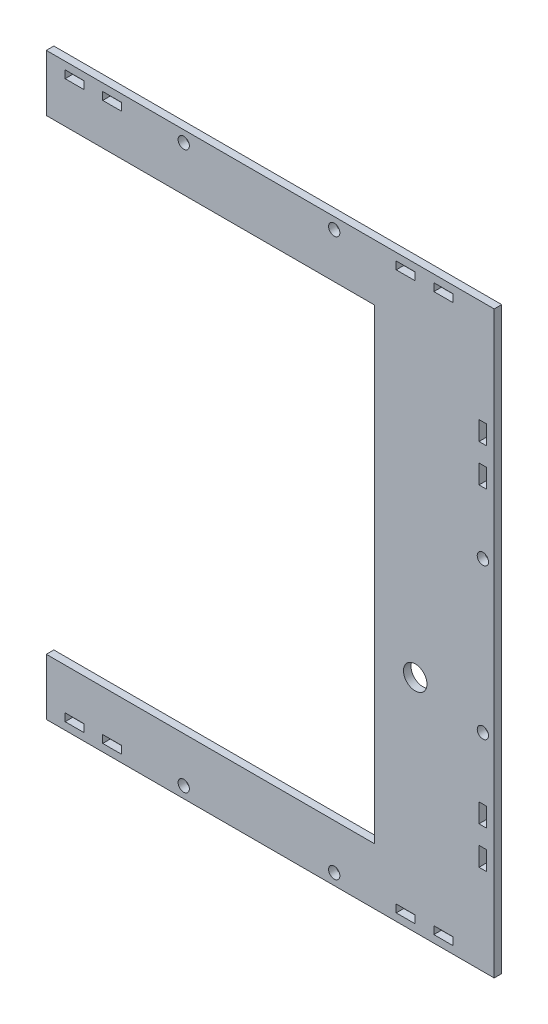
SolidWorks part; units mm, degrees
ref_plane "前视基准面" through (0, 0, 0) normal (0, 0, 1) x (1, 0, 0)
ref_plane "上视基准面" through (0, 0, 0) normal (0, 1, 0) x (1, 0, 0)
ref_plane "右视基准面" through (0, 0, 0) normal (1, 0, 0) x (0, 0, -1)
sketch "草图1" plane through (0, 0, 0) normal (0, 0, 1) x (1, 0, 0)
  line L0 (-46.0613, -2.3972) -> (-51.1113, -0.3472) construction
  line L5 (36.8887, -0.3472) -> (41.9387, -0.3472)
  line L6 (36.8887, -0.3472) -> (36.8887, -2.3972)
  line L11 (36.8887, -2.3972) -> (41.9387, -2.3972)
  line L12 (41.9387, -0.3472) -> (41.9387, -2.3972)
  line L13 (36.8887, -0.3472) -> (41.9387, -2.3972) construction
  line L14 (36.8887, -2.3972) -> (41.9387, -0.3472) construction
  line L15 (46.8887, -0.3472) -> (51.9387, -0.3472)
  line L25 (46.8887, -0.3472) -> (46.8887, -2.3972)
  line L30 (46.8887, -2.3972) -> (51.9387, -2.3972)
  line L31 (51.9387, -0.3472) -> (51.9387, -2.3972)
  line L36 (46.8887, -0.3472) -> (51.9387, -2.3972) construction
  line L37 (46.8887, -2.3972) -> (51.9387, -0.3472) construction
  line L38 (-46.0613, -0.3472) -> (-51.1113, -2.3972) construction
  line L39 (-36.0613, -2.3972) -> (-41.1113, -0.3472) construction
  line L40 (-36.0613, -0.3472) -> (-41.1113, -2.3972) construction
  line L55 (-51.1113, -0.3472) -> (-51.1113, -2.3972)
  line L60 (-46.0613, -2.3972) -> (-51.1113, -2.3972)
  line L61 (-46.0613, -0.3472) -> (-46.0613, -2.3972)
  line L66 (-46.0613, -0.3472) -> (-51.1113, -0.3472)
  line L67 (-41.1113, -0.3472) -> (-41.1113, -2.3972)
  line L68 (-36.0613, -2.3972) -> (-41.1113, -2.3972)
  line L69 (-36.0613, -0.3472) -> (-36.0613, -2.3972)
  line L70 (-36.0613, -0.3472) -> (-41.1113, -0.3472)
  line L81 (-48.5863, -1.3722) -> (49.4137, -1.3722) construction
  line L82 (-19.5863, -149.3722) -> (-8.6103, -149.3722) construction
  line L83 (-46.0613, -150.3972) -> (-51.1113, -148.3472) construction
  line L84 (36.8887, -148.3472) -> (41.9387, -148.3472)
  line L85 (36.8887, -148.3472) -> (36.8887, -150.3972)
  line L86 (36.8887, -150.3972) -> (41.9387, -150.3972)
  line L87 (41.9387, -148.3472) -> (41.9387, -150.3972)
  line L88 (36.8887, -148.3472) -> (41.9387, -150.3972) construction
  line L89 (36.8887, -150.3972) -> (41.9387, -148.3472) construction
  line L90 (46.8887, -148.3472) -> (51.9387, -148.3472)
  line L91 (46.8887, -148.3472) -> (46.8887, -150.3972)
  line L92 (46.8887, -150.3972) -> (51.9387, -150.3972)
  line L93 (51.9387, -148.3472) -> (51.9387, -150.3972)
  line L94 (46.8887, -148.3472) -> (51.9387, -150.3972) construction
  line L95 (46.8887, -150.3972) -> (51.9387, -148.3472) construction
  line L96 (-46.0613, -148.3472) -> (-51.1113, -150.3972) construction
  line L97 (-36.0613, -150.3972) -> (-41.1113, -148.3472) construction
  line L98 (-36.0613, -148.3472) -> (-41.1113, -150.3972) construction
  line L99 (-51.1113, -148.3472) -> (-51.1113, -150.3972)
  line L100 (-46.0613, -150.3972) -> (-51.1113, -150.3972)
  line L101 (-46.0613, -148.3472) -> (-46.0613, -150.3972)
  line L102 (-46.0613, -148.3472) -> (-51.1113, -148.3472)
  line L103 (-41.1113, -148.3472) -> (-41.1113, -150.3972)
  line L104 (-36.0613, -150.3972) -> (-41.1113, -150.3972)
  line L105 (-36.0613, -148.3472) -> (-36.0613, -150.3972)
  line L106 (-36.0613, -148.3472) -> (-41.1113, -148.3472)
  line L107 (59.9198, -57.3722) -> (59.9198, -97.3722) construction
  line L108 (-56.1113, -13.3722) -> (31.071, -13.3722)
  line L109 (-56.1113, 1.6278) -> (62.9198, 1.6278)
  line L110 (-56.1113, 1.6278) -> (-56.1113, -152.3722) construction
  line L111 (-56.1113, -152.3722) -> (62.9198, -152.3722) construction
  line L112 (62.9198, 1.6278) -> (62.9198, -152.3722)
  line L113 (60.9448, -123.8472) -> (58.8948, -128.8972) construction
  line L114 (58.8948, -40.8972) -> (58.8948, -35.8472)
  line L115 (58.8948, -40.8972) -> (60.9448, -40.8972)
  line L116 (60.9448, -40.8972) -> (60.9448, -35.8472)
  line L117 (58.8948, -35.8472) -> (60.9448, -35.8472)
  line L118 (58.8948, -40.8972) -> (60.9448, -35.8472) construction
  line L119 (60.9448, -40.8972) -> (58.8948, -35.8472) construction
  line L120 (58.8948, -30.8972) -> (58.8948, -25.8472)
  line L121 (58.8948, -30.8972) -> (60.9448, -30.8972)
  line L122 (60.9448, -30.8972) -> (60.9448, -25.8472)
  line L123 (58.8948, -25.8472) -> (60.9448, -25.8472)
  line L124 (58.8948, -30.8972) -> (60.9448, -25.8472) construction
  line L125 (60.9448, -30.8972) -> (58.8948, -25.8472) construction
  line L126 (58.8948, -123.8472) -> (60.9448, -128.8972) construction
  line L127 (60.9448, -113.8472) -> (58.8948, -118.8972) construction
  line L128 (58.8948, -113.8472) -> (60.9448, -118.8972) construction
  line L129 (58.8948, -128.8972) -> (60.9448, -128.8972)
  line L130 (60.9448, -123.8472) -> (60.9448, -128.8972)
  line L131 (58.8948, -123.8472) -> (60.9448, -123.8472)
  line L132 (58.8948, -123.8472) -> (58.8948, -128.8972)
  line L133 (58.8948, -118.8972) -> (60.9448, -118.8972)
  line L134 (60.9448, -113.8472) -> (60.9448, -118.8972)
  line L135 (58.8948, -113.8472) -> (60.9448, -113.8472)
  line L136 (58.8948, -113.8472) -> (58.8948, -118.8972)
  line L137 (31.071, -13.3722) -> (31.071, -137.3722)
  line L138 (31.071, -137.3722) -> (-56.1113, -137.3722)
  line L139 (-56.1113, -137.3722) -> (-56.1113, -152.3722)
  line L140 (-56.1113, -13.3722) -> (-56.1113, 1.6278)
  line L141 (62.9198, -152.3722) -> (-56.1113, -152.3722)
  circle A6 centre (-19.5863, -1.3722) radius 1.5
  circle A7 centre (20.4137, -1.3722) radius 1.5
  circle A9 centre (-19.5863, -149.3722) radius 1.5
  circle A10 centre (20.4137, -149.3722) radius 1.5
  circle A11 centre (59.9198, -97.3722) radius 1.5
  circle A12 centre (59.9198, -57.3722) radius 1.5
  circle A13 centre (41.9387, -93.6781) radius 3.1213
  point P8 (-38.5863, -1.3722)
  point P13 (39.4137, -1.3722)
  point P35 (-38.5863, -149.3722)
  point P40 (39.4137, -149.3722)
  point P54 (3.4042, -152.3722)
  point P80 (101.1063, -340.4435)
  dimension "D1" = 148
  dimension "D2" = 3
  dimension "D4" = 3
  dimension "D5" = 5
  dimension "D6" = 15
  dimension "D7" = 15
extrude "凸台-拉伸1" add sketch "草图1" along normal blind 2
